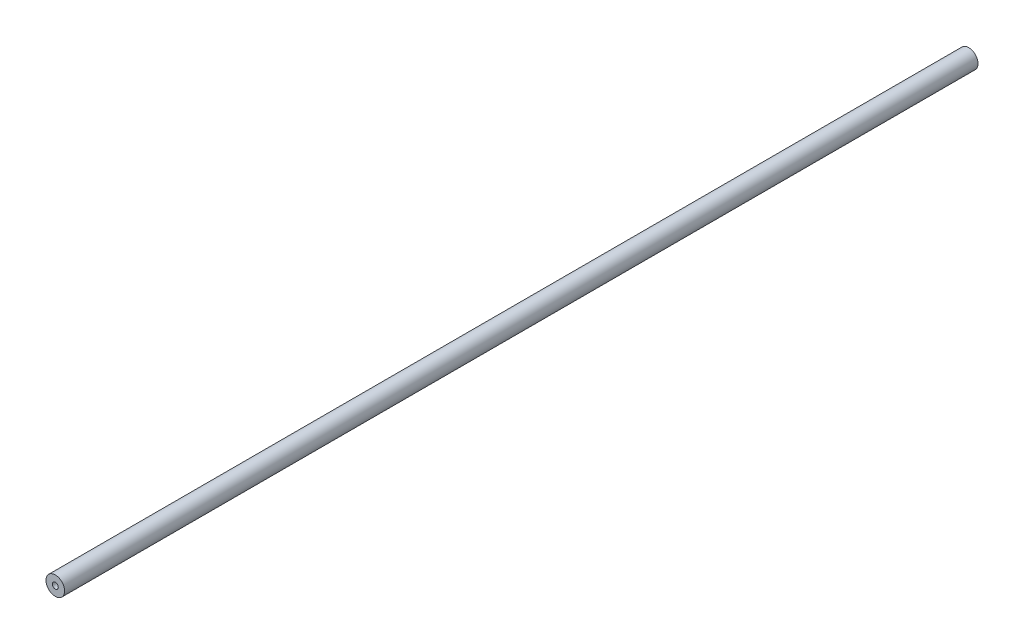
SolidWorks part; units mm, degrees
material "6061-T6 (SS)"
ref_plane "Front Plane" through (0, 0, 0) normal (0, 0, 1) x (1, 0, 0)
ref_plane "Top Plane" through (0, 0, 0) normal (0, 1, 0) x (1, 0, 0)
ref_plane "Right Plane" through (0, 0, 0) normal (1, 0, 0) x (0, 0, -1)
sketch "Sketch1" plane through (0, 0, 0) normal (0, 0, 1) x (1, 0, 0)
  circle A0 centre (0, 0) radius 6.35
  dimension "D1" = 12.7
extrude "Boss-Extrude1" add sketch "Sketch1" along normal blind 622.808
hole_wizard "#10-32 Tapped Hole1" positions "Sketch3" profile "Sketch2" tap size "#10-32" standard "ANSI Inch"
sketch "Sketch3" plane through (0, 0, 622.808) normal (0, 0, 1) x (1, 0, 0)
  point P0 (0, 0)
sketch "Sketch2" plane through (0, 0, 622.808) normal (1, 0, 0) x (0, -1, 0)
  line L0 (0, 0) -> (0, 14.9293)
  line L1 (0, 14.9293) -> (2.0193, 13.716)
  line L2 (2.0193, 13.716) -> (2.0193, 0)
  line L5 (2.0193, 0) -> (0, 0)
  line L10 (0, 14.9293) -> (-2.0193, 13.716) construction
  line L11 (0, -6.35) -> (0, 107.95) construction
  dimension "Tap Drill Dia." = 4.0386
  dimension "Tap Drill Depth" = 13.716
  dimension "Drill Angle" = 118
cosmetic thread "Hole Thread1"
hole_wizard "#10-32 Tapped Hole2" positions "Sketch5" profile "Sketch4" tap size "#10-32" standard "ANSI Inch"
sketch "Sketch5" plane through (0, 0, 0) normal (0, 0, -1) x (-1, 0, 0)
  point P0 (0, 0)
sketch "Sketch4" plane through (0, 0, 0) normal (1, 0, 0) x (0, 1, 0)
  line L0 (0, 0) -> (0, 14.9293)
  line L1 (0, 14.9293) -> (2.0193, 13.716)
  line L2 (2.0193, 13.716) -> (2.0193, 0)
  line L5 (2.0193, 0) -> (0, 0)
  line L10 (0, 14.9293) -> (-2.0193, 13.716) construction
  line L11 (0, -6.35) -> (0, 107.95) construction
  dimension "Tap Drill Dia." = 4.0386
  dimension "Tap Drill Depth" = 13.716
  dimension "Drill Angle" = 118
cosmetic thread "Hole Thread2" parameters "D1"=9.652, "D2"=4.826
